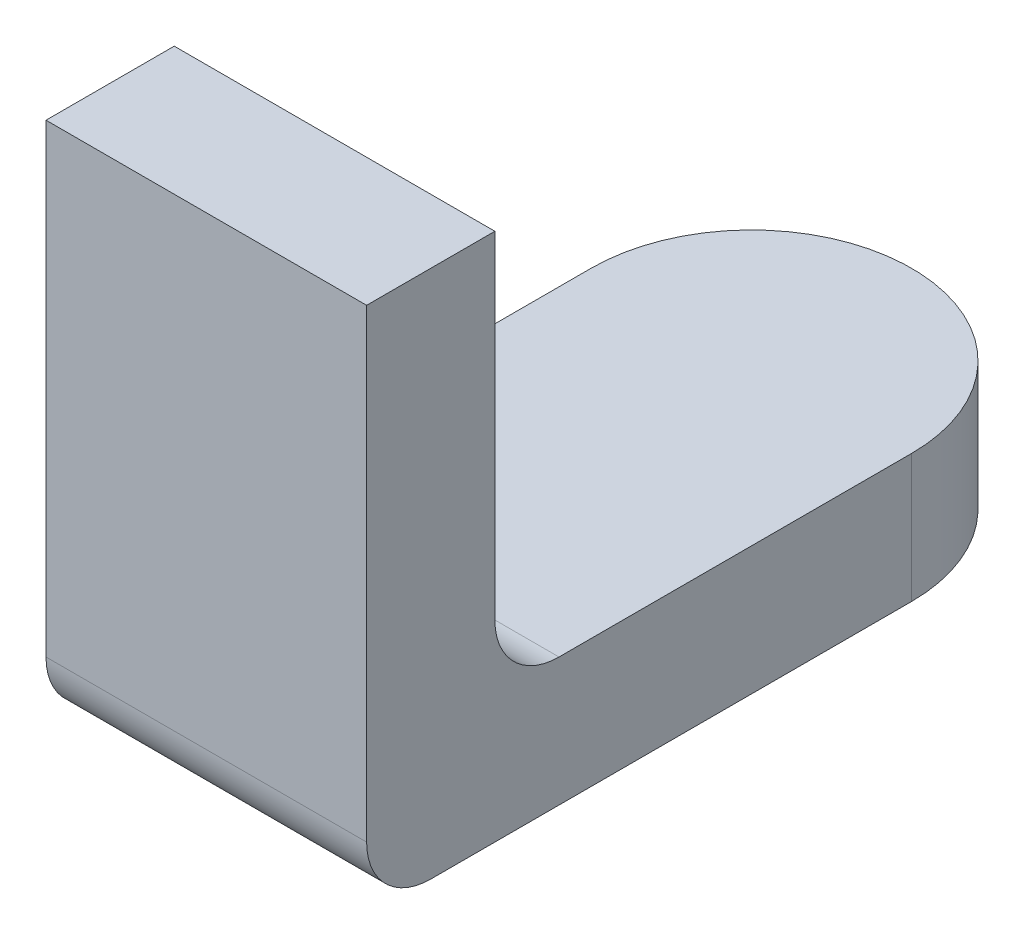
SolidWorks part; units mm, degrees
ref_plane "Plano frontal" through (0, 0, 0) normal (0, 0, 1) x (1, 0, 0)
ref_plane "Plano superior" through (0, 0, 0) normal (0, 1, 0) x (1, 0, 0)
ref_plane "Plano direito" through (0, 0, 0) normal (1, 0, 0) x (0, 0, -1)
sketch "Esboço1" plane through (0, 0, 0) normal (0, 1, 0) x (1, 0, 0)
  line L1 (0, 0) -> (20, 0)
  line L2 (0, 0) -> (0, 34)
  line L4 (20, 0) -> (20, 34)
  arc A0 (0, 34) -> (20, 34) centre (10, 34) cw
  point P1 (0, 38.1361)
  point P2 (0, 0)
  point P5 (10, 44)
  point P9 (0, 0)
  dimension "D2" = 44
  dimension "D1" = 20
extrude "Ressalto-extrusão1" add sketch "Esboço1" along normal blind 8
sketch "Esboço2" plane through (0, 8, 0) normal (0, 1, 0) x (1, 0, 0)
  line L0 (20, 0) -> (20, 34) construction
  line L1 (0, 0) -> (20, 0)
  line L2 (0, 0) -> (0, 8)
  line L3 (0, 8) -> (20, 8)
  line L4 (20, 0) -> (20, 8)
  dimension "D1" = 8
extrude "Ressalto-extrusão2" add sketch "Esboço2" along normal offset from surface (25 mm away) 33 up to face at (10, 0, -19.5)
fillet "Filete1" radius 4 2 edges at (10, 8, -8) (10, 0, 0)
